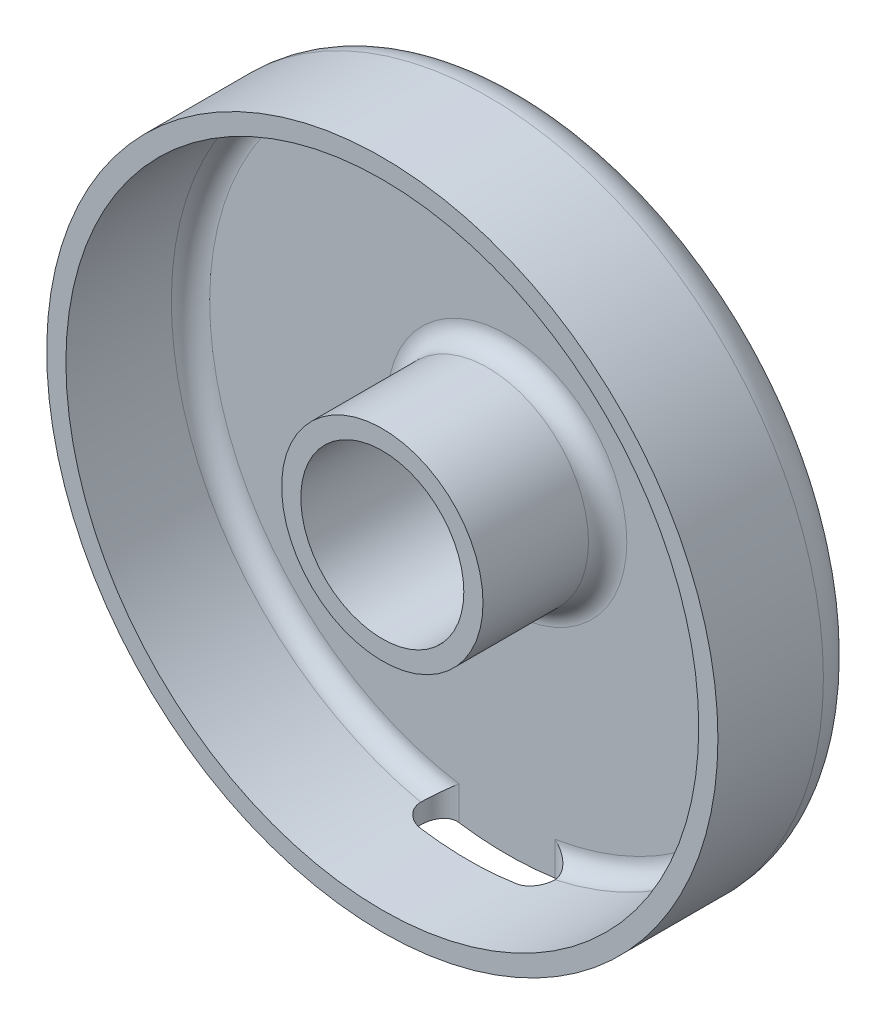
SolidWorks part; units mm, degrees
ref_plane "Alzado" through (0, 0, 0) normal (0, 0, 1) x (1, 0, 0)
ref_plane "Planta" through (0, 0, 0) normal (0, 1, 0) x (1, 0, 0)
ref_plane "Vista lateral" through (0, 0, 0) normal (1, 0, 0) x (0, 0, -1)
sketch "Croquis1" plane through (0, 0, 0) normal (0, 0, 1) x (1, 0, 0)
  circle A0 centre (0, 0) radius 35
  dimension "D1" = 70
extrude "Saliente-Extruir1" add sketch "Croquis1" along normal blind 15
sketch "Croquis2" plane through (0, 0, 15) normal (0, 0, 1) x (1, 0, 0)
  circle A0 centre (0, 0) radius 8.5
  dimension "D1" = 17
extrude "Cortar-Extruir1" cut sketch "Croquis2" against normal through all
shell "Vaciado1" thickness 2
fillet "Redondeo1" radius 2 2 edges at (10.5, 0, 2) (33, 0, 2)
fillet "Redondeo2" radius 4 1 edges at (35, 0, 0)
sketch "Croquis3" plane through (0, 0, 0) normal (0, 1, 0) x (1, 0, 0)
  line L0 (-5, -4) -> (5, -4) construction
  line L1 (-5, -2) -> (5, -2)
  line L2 (-5, -6) -> (5, -6)
  line L3 (0, 0) -> (0, -15) construction
  line L4 (-35, -15) -> (35, -15) construction
  line L5 (35, -4) -> (-35, -4) construction
  arc A0 (-5, -2) -> (-5, -6) centre (-5, -4) ccw
  arc A1 (5, -6) -> (5, -2) centre (5, -4) ccw
  point P2 (0, -4)
  dimension "D1" = 2
  dimension "D2" = 10
extrude "Cortar-Extruir2" cut sketch "Croquis3" against normal through all from offset 25
